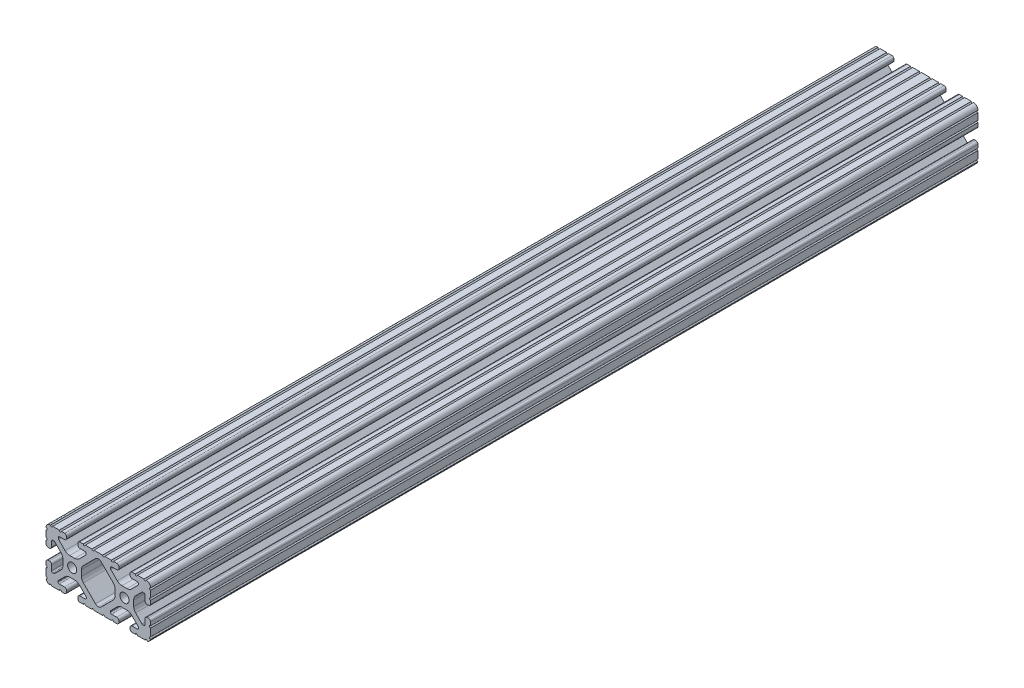
SolidWorks part; units mm, degrees
material "6061 Alloy"
ref_plane "Front Plane" through (0, 0, 0) normal (0, 0, 1) x (1, 0, 0)
ref_plane "Top Plane" through (0, 0, 0) normal (0, 1, 0) x (1, 0, 0)
ref_plane "Right Plane" through (0, 0, 0) normal (1, 0, 0) x (0, 0, -1)
sketch "Sketch1" plane through (0, 0, 0) normal (0, 0, 1) x (1, 0, 0)
  line L0 (-3.1211, -19.05) -> (3.1211, -19.05)
  line L1 (-38.1, 10.287) -> (-38.1, 14.3752)
  line L2 (0, -34.5561) -> (0, 32.8014) construction
  line L3 (-38.1, 0) -> (0, 0) construction
  line L4 (-38.1, 9.5497) -> (-38.1, 10.287)
  line L5 (-19.05, 19.05) -> (-19.05, -20.2827) construction
  line L6 (0, -15.1247) -> (0, -15.1131) construction
  line L7 (9.1761, 12.9058) -> (13.8525, 8.2294)
  line L8 (8.9158, 14.097) -> (8.9158, 13.5344)
  line L9 (13.4112, 14.986) -> (9.8048, 14.986)
  line L10 (14.986, 17.4968) -> (14.986, 16.5608)
  line L11 (10.9975, 19.05) -> (13.4328, 19.05)
  line L12 (8.6331, 19.05) -> (9.4735, 19.05)
  line L13 (4.6451, 19.05) -> (8.6331, 19.05)
  line L14 (31.792, 10.0266) -> (27.1976, 5.4321)
  line L15 (33.147, 10.287) -> (32.4207, 10.287)
  line L16 (29.2071, 19.05) -> (33.2963, 19.05)
  line L17 (28.4698, 19.05) -> (29.2071, 19.05)
  line L18 (-38.1, 5.6388) -> (-38.1, 8.0257)
  line L19 (24.5589, 19.05) -> (26.9458, 19.05)
  line L20 (23.114, 16.5608) -> (23.114, 17.4806)
  line L21 (28.2952, 14.986) -> (24.6888, 14.986)
  line L22 (29.1842, 13.5344) -> (29.1842, 14.097)
  line L23 (-34.036, 9.398) -> (-34.036, 5.6388)
  line L24 (-35.6108, 4.064) -> (-36.5252, 4.064)
  line L25 (24.2475, 8.2294) -> (28.9239, 12.9058)
  line L26 (25.8064, -2.0735) -> (25.8064, 2.0735)
  line L27 (35.6108, 4.064) -> (36.5252, 4.064)
  line L28 (34.036, 9.398) -> (34.036, 5.6388)
  line L29 (38.1, 5.6388) -> (38.1, 8.0257)
  line L30 (38.1, 9.5497) -> (38.1, 10.287)
  line L31 (38.1, 10.287) -> (38.1, 14.3752)
  line L32 (17.2111, 6.8382) -> (20.8889, 6.8382)
  line L33 (2.077, 14.2576) -> (10.9024, 5.4321)
  line L34 (-31.792, -10.0266) -> (-27.1976, -5.4321)
  line L35 (-33.147, -10.287) -> (-32.4207, -10.287)
  line L36 (-29.2071, -19.05) -> (-34.0473, -19.05)
  line L37 (-28.4698, -19.05) -> (-29.2071, -19.05)
  line L38 (-24.6888, -19.05) -> (-26.9458, -19.05)
  line L39 (12.2936, -2.0735) -> (12.2936, 2.0735)
  line L40 (-23.114, -16.5608) -> (-23.114, -17.4752)
  line L41 (-28.448, -14.986) -> (-24.6888, -14.986)
  line L42 (-29.337, -13.6872) -> (-29.337, -14.097)
  line L43 (2.077, -14.2576) -> (10.9024, -5.4321)
  line L44 (-3.1211, 19.05) -> (3.1211, 19.05)
  line L45 (8.763, -14.097) -> (8.763, -13.6872)
  line L46 (-24.2475, -8.2294) -> (-29.0766, -13.0586)
  line L47 (-35.6108, -4.064) -> (-36.5252, -4.064)
  line L48 (-34.036, -9.398) -> (-34.036, -5.6388)
  line L49 (-38.1, -5.6388) -> (-38.1, -8.0257)
  line L50 (-38.1, -9.5497) -> (-38.1, -10.287)
  line L51 (-38.1, -10.287) -> (-38.1, -15.036)
  line L52 (17.2111, -6.8382) -> (20.8889, -6.8382)
  line L53 (38.1, -10.287) -> (38.1, -15.036)
  line L54 (38.1, -9.5497) -> (38.1, -10.287)
  line L55 (38.1, -5.6388) -> (38.1, -8.0257)
  line L56 (34.036, -9.398) -> (34.036, -5.6388)
  line L57 (35.6108, -4.064) -> (36.5252, -4.064)
  line L58 (24.2475, -8.2294) -> (29.0766, -13.0586)
  line L59 (29.337, -13.6872) -> (29.337, -14.097)
  line L60 (-17.2111, -6.8382) -> (-20.8889, -6.8382)
  line L61 (-9.0234, -13.0586) -> (-13.8525, -8.2294)
  line L62 (-8.763, -14.097) -> (-8.763, -13.6872)
  line L63 (-13.4112, -14.986) -> (-9.652, -14.986)
  line L64 (-14.986, -17.4752) -> (-14.986, -16.5608)
  line L65 (-10.9975, -19.05) -> (-13.4112, -19.05)
  line L66 (28.448, -14.986) -> (24.6888, -14.986)
  line L67 (23.114, -16.5608) -> (23.114, -17.4752)
  line L68 (24.6888, -19.05) -> (26.9458, -19.05)
  line L69 (28.4698, -19.05) -> (29.2071, -19.05)
  line L70 (29.2071, -19.05) -> (34.0473, -19.05)
  line L71 (-8.6331, -19.05) -> (-9.4735, -19.05)
  line L72 (33.147, -10.287) -> (32.4207, -10.287)
  line L73 (31.792, -10.0266) -> (27.1976, -5.4321)
  line L74 (-4.6451, -19.05) -> (-8.6331, -19.05)
  line L75 (9.0234, -13.0586) -> (13.8525, -8.2294)
  line L76 (13.4112, -14.986) -> (9.652, -14.986)
  line L77 (-2.077, -14.2576) -> (-10.9024, -5.4321)
  line L78 (14.986, -17.4752) -> (14.986, -16.5608)
  line L79 (10.9975, -19.05) -> (13.4112, -19.05)
  line L80 (4.6451, -19.05) -> (8.6331, -19.05)
  line L81 (8.6331, -19.05) -> (9.4735, -19.05)
  line L83 (-12.2936, -2.0735) -> (-12.2936, 2.0735)
  line L84 (-25.8064, -2.0735) -> (-25.8064, 2.0735)
  line L85 (-2.077, 14.2576) -> (-10.9024, 5.4321)
  line L87 (-4.6451, 19.05) -> (-8.6331, 19.05)
  line L88 (-8.6331, 19.05) -> (-9.4735, 19.05)
  line L89 (-10.9975, 19.05) -> (-13.4328, 19.05)
  line L90 (-14.986, 17.4968) -> (-14.986, 16.5608)
  line L91 (-13.4112, 14.986) -> (-9.8048, 14.986)
  line L92 (-8.9158, 14.097) -> (-8.9158, 13.5344)
  line L93 (-9.1761, 12.9058) -> (-13.8525, 8.2294)
  line L94 (-17.2111, 6.8382) -> (-20.8889, 6.8382)
  line L95 (-24.2475, 8.2294) -> (-28.9239, 12.9058)
  line L96 (-29.1842, 13.5344) -> (-29.1842, 14.097)
  line L97 (-28.2952, 14.986) -> (-24.6888, 14.986)
  line L98 (-23.114, 16.5608) -> (-23.114, 17.4806)
  line L99 (-24.5589, 19.05) -> (-26.9458, 19.05)
  line L100 (-28.4698, 19.05) -> (-29.2071, 19.05)
  line L101 (-29.2071, 19.05) -> (-33.2963, 19.05)
  line L109 (-33.147, 10.287) -> (-32.4207, 10.287)
  line L165 (-31.792, 10.0266) -> (-27.1976, 5.4321)
  arc A0 (-38.1376, 15.8983) -> (-38.1, 14.3752) centre (-38.1, 15.1372) cw
  arc A1 (-38.1, 9.5497) -> (-38.1, 8.0257) centre (-38.1, 8.7877) cw
  arc A2 (9.1761, 12.9058) -> (8.9158, 13.5344) centre (9.8048, 13.5344) cw
  arc A3 (8.9158, 14.097) -> (9.8048, 14.986) centre (9.8048, 14.097) cw
  arc A4 (-36.5252, 4.064) -> (-38.1, 5.6388) centre (-36.5252, 5.6388) cw
  arc A5 (14.986, 16.5608) -> (13.4112, 14.986) centre (13.4112, 16.5608) cw
  arc A6 (13.4328, 19.05) -> (14.986, 17.4968) centre (13.4328, 17.4968) cw
  arc A7 (10.9975, 19.05) -> (9.4735, 19.05) centre (10.2355, 19.05) cw
  arc A8 (4.6451, 19.05) -> (3.1211, 19.05) centre (3.8831, 19.05) cw
  arc A9 (0, 15.1131) -> (2.077, 14.2576) centre (0.0116, 12.1921) cw
  arc A10 (25.8064, 2.0735) -> (27.1976, 5.4321) centre (30.5562, 2.0735) cw
  arc A11 (31.792, 10.0266) -> (32.4207, 10.287) centre (32.4207, 9.398) cw
  arc A12 (33.147, 10.287) -> (34.036, 9.398) centre (33.147, 9.398) cw
  arc A13 (34.8195, 19.0968) -> (38.1376, 15.8983) centre (34.903, 15.8631) cw
  arc A14 (34.8195, 19.0968) -> (33.2963, 19.05) centre (34.0579, 19.0734) cw
  arc A15 (28.4698, 19.05) -> (26.9458, 19.05) centre (27.7078, 19.05) cw
  arc A16 (23.114, 17.4806) -> (24.5589, 19.05) centre (24.6888, 17.4806) cw
  arc A17 (24.6888, 14.986) -> (23.114, 16.5608) centre (24.6888, 16.5608) cw
  arc A18 (28.2952, 14.986) -> (29.1842, 14.097) centre (28.2952, 14.097) cw
  arc A19 (29.1842, 13.5344) -> (28.9239, 12.9058) centre (28.2952, 13.5344) cw
  arc A20 (-35.5713, -19.05) -> (-38.1, -16.56) centre (-34.9455, -15.8855) cw
  arc A21 (34.036, 5.6388) -> (35.6108, 4.064) centre (35.6108, 5.6388) ccw
  arc A22 (36.5252, 4.064) -> (38.1, 5.6388) centre (36.5252, 5.6388) ccw
  arc A23 (38.1, 9.5497) -> (38.1, 8.0257) centre (38.1, 8.7877) ccw
  arc A24 (24.2475, 8.2294) -> (20.8889, 6.8382) centre (20.8889, 11.588) cw
  arc A25 (17.2111, 6.8382) -> (13.8525, 8.2294) centre (17.2111, 11.588) cw
  arc A26 (10.9024, 5.4321) -> (12.2936, 2.0735) centre (7.5438, 2.0735) cw
  arc A27 (0, -15.1131) -> (2.077, -14.2576) centre (0.0116, -12.1921) ccw
  arc A28 (-34.036, 5.6388) -> (-35.6108, 4.064) centre (-35.6108, 5.6388) cw
  arc A29 (-25.8064, -2.0735) -> (-27.1976, -5.4321) centre (-30.5562, -2.0735) cw
  arc A30 (-31.792, -10.0266) -> (-32.4207, -10.287) centre (-32.4207, -9.398) cw
  arc A31 (-33.147, -10.287) -> (-34.036, -9.398) centre (-33.147, -9.398) cw
  arc A33 (-35.5713, -19.05) -> (-34.0473, -19.05) centre (-34.8093, -19.05) cw
  arc A34 (-28.4698, -19.05) -> (-26.9458, -19.05) centre (-27.7078, -19.05) cw
  arc A35 (10.9024, -5.4321) -> (12.2936, -2.0735) centre (7.5438, -2.0735) ccw
  circle A36 centre (19.05, 0) radius 3.3274
  arc A37 (-23.114, -17.4752) -> (-24.6888, -19.05) centre (-24.6888, -17.4752) cw
  arc A38 (-24.6888, -14.986) -> (-23.114, -16.5608) centre (-24.6888, -16.5608) cw
  arc A39 (-28.448, -14.986) -> (-29.337, -14.097) centre (-28.448, -14.097) cw
  arc A40 (-29.337, -13.6872) -> (-29.0766, -13.0586) centre (-28.448, -13.6872) cw
  arc A41 (-24.2475, -8.2294) -> (-20.8889, -6.8382) centre (-20.8889, -11.588) cw
  arc A42 (-34.036, -5.6388) -> (-35.6108, -4.064) centre (-35.6108, -5.6388) ccw
  arc A43 (-36.5252, -4.064) -> (-38.1, -5.6388) centre (-36.5252, -5.6388) ccw
  arc A44 (-38.1, -9.5497) -> (-38.1, -8.0257) centre (-38.1, -8.7877) ccw
  arc A45 (-38.1, -16.56) -> (-38.1, -15.036) centre (-38.1, -15.798) ccw
  arc A46 (38.1, -16.56) -> (38.1, -15.036) centre (38.1, -15.798) cw
  arc A47 (38.1, -9.5497) -> (38.1, -8.0257) centre (38.1, -8.7877) cw
  arc A48 (36.5252, -4.064) -> (38.1, -5.6388) centre (36.5252, -5.6388) cw
  arc A49 (34.036, -5.6388) -> (35.6108, -4.064) centre (35.6108, -5.6388) cw
  arc A50 (24.2475, -8.2294) -> (20.8889, -6.8382) centre (20.8889, -11.588) ccw
  arc A51 (29.337, -13.6872) -> (29.0766, -13.0586) centre (28.448, -13.6872) ccw
  arc A52 (28.448, -14.986) -> (29.337, -14.097) centre (28.448, -14.097) ccw
  arc A53 (24.6888, -14.986) -> (23.114, -16.5608) centre (24.6888, -16.5608) ccw
  arc A54 (-17.2111, -6.8382) -> (-13.8525, -8.2294) centre (-17.2111, -11.588) cw
  arc A55 (-9.0234, -13.0586) -> (-8.763, -13.6872) centre (-9.652, -13.6872) cw
  arc A56 (-8.763, -14.097) -> (-9.652, -14.986) centre (-9.652, -14.097) cw
  arc A57 (-14.986, -16.5608) -> (-13.4112, -14.986) centre (-13.4112, -16.5608) cw
  arc A58 (-13.4112, -19.05) -> (-14.986, -17.4752) centre (-13.4112, -17.4752) cw
  arc A59 (-10.9975, -19.05) -> (-9.4735, -19.05) centre (-10.2355, -19.05) cw
  arc A60 (-4.6451, -19.05) -> (-3.1211, -19.05) centre (-3.8831, -19.05) cw
  arc A61 (23.114, -17.4752) -> (24.6888, -19.05) centre (24.6888, -17.4752) ccw
  arc A62 (28.4698, -19.05) -> (26.9458, -19.05) centre (27.7078, -19.05) ccw
  arc A63 (35.5713, -19.05) -> (34.0473, -19.05) centre (34.8093, -19.05) ccw
  arc A64 (35.5713, -19.05) -> (38.1, -16.56) centre (34.9379, -15.8778) ccw
  arc A65 (33.147, -10.287) -> (34.036, -9.398) centre (33.147, -9.398) ccw
  arc A66 (31.792, -10.0266) -> (32.4207, -10.287) centre (32.4207, -9.398) ccw
  arc A67 (-10.9024, -5.4321) -> (-12.2936, -2.0735) centre (-7.5438, -2.0735) cw
  arc A68 (0, -15.1131) -> (-2.077, -14.2576) centre (-0.0116, -12.1921) cw
  arc A69 (0, 15.1131) -> (-2.077, 14.2576) centre (-0.0116, 12.1921) ccw
  arc A70 (-10.9024, 5.4321) -> (-12.2936, 2.0735) centre (-7.5438, 2.0735) ccw
  arc A71 (25.8064, -2.0735) -> (27.1976, -5.4321) centre (30.5562, -2.0735) ccw
  arc A72 (9.0234, -13.0586) -> (8.763, -13.6872) centre (9.652, -13.6872) ccw
  arc A73 (8.763, -14.097) -> (9.652, -14.986) centre (9.652, -14.097) ccw
  arc A74 (17.2111, -6.8382) -> (13.8525, -8.2294) centre (17.2111, -11.588) ccw
  arc A75 (13.4112, -19.05) -> (14.986, -17.4752) centre (13.4112, -17.4752) ccw
  arc A76 (14.986, -16.5608) -> (13.4112, -14.986) centre (13.4112, -16.5608) ccw
  arc A77 (-4.6451, 19.05) -> (-3.1211, 19.05) centre (-3.8831, 19.05) ccw
  arc A78 (-10.9975, 19.05) -> (-9.4735, 19.05) centre (-10.2355, 19.05) ccw
  arc A79 (-13.4328, 19.05) -> (-14.986, 17.4968) centre (-13.4328, 17.4968) ccw
  arc A80 (-14.986, 16.5608) -> (-13.4112, 14.986) centre (-13.4112, 16.5608) ccw
  arc A81 (-8.9158, 14.097) -> (-9.8048, 14.986) centre (-9.8048, 14.097) ccw
  arc A82 (-9.1761, 12.9058) -> (-8.9158, 13.5344) centre (-9.8048, 13.5344) ccw
  arc A83 (-17.2111, 6.8382) -> (-13.8525, 8.2294) centre (-17.2111, 11.588) ccw
  arc A84 (-24.2475, 8.2294) -> (-20.8889, 6.8382) centre (-20.8889, 11.588) ccw
  arc A85 (-29.1842, 13.5344) -> (-28.9239, 12.9058) centre (-28.2952, 13.5344) ccw
  arc A86 (-28.2952, 14.986) -> (-29.1842, 14.097) centre (-28.2952, 14.097) ccw
  arc A87 (-24.6888, 14.986) -> (-23.114, 16.5608) centre (-24.6888, 16.5608) ccw
  arc A88 (-23.114, 17.4806) -> (-24.5589, 19.05) centre (-24.6888, 17.4806) ccw
  arc A89 (-28.4698, 19.05) -> (-26.9458, 19.05) centre (-27.7078, 19.05) ccw
  arc A90 (-34.8195, 19.0968) -> (-33.2963, 19.05) centre (-34.0579, 19.0734) ccw
  arc A91 (-34.8195, 19.0968) -> (-38.1376, 15.8983) centre (-34.903, 15.8631) ccw
  arc A92 (4.6451, -19.05) -> (3.1211, -19.05) centre (3.8831, -19.05) ccw
  arc A93 (10.9975, -19.05) -> (9.4735, -19.05) centre (10.2355, -19.05) ccw
  arc A94 (38.1376, 15.8983) -> (38.1, 14.3752) centre (38.1, 15.1372) ccw
  arc A96 (-33.147, 10.287) -> (-34.036, 9.398) centre (-33.147, 9.398) ccw
  arc A97 (-31.792, 10.0266) -> (-32.4207, 10.287) centre (-32.4207, 9.398) ccw
  arc A98 (-25.8064, 2.0735) -> (-27.1976, 5.4321) centre (-30.5562, 2.0735) ccw
  circle A101 centre (-19.05, 0) radius 3.3274
  point P34 (0, 19.05)
  point P79 (25.6765, 0)
  point P274 (0, -19.05)
  point P282 (-25.6765, 0)
  point P283 (-12.2936, 0)
  dimension "D1" = 38.1
  dimension "D4" = 6.6548
  dimension "D10" = 4.064
  dimension "D2" = 76.2
  dimension "D3" = 38.1
  dimension "D5" = 8.128
  dimension "D6" = 20.574
  dimension "D7" = 12.2936
  dimension "D8" = 4.064
  dimension "D9" = 4.064
extrude "Extrude1" add sketch "Sketch1" against normal blind 603.25
